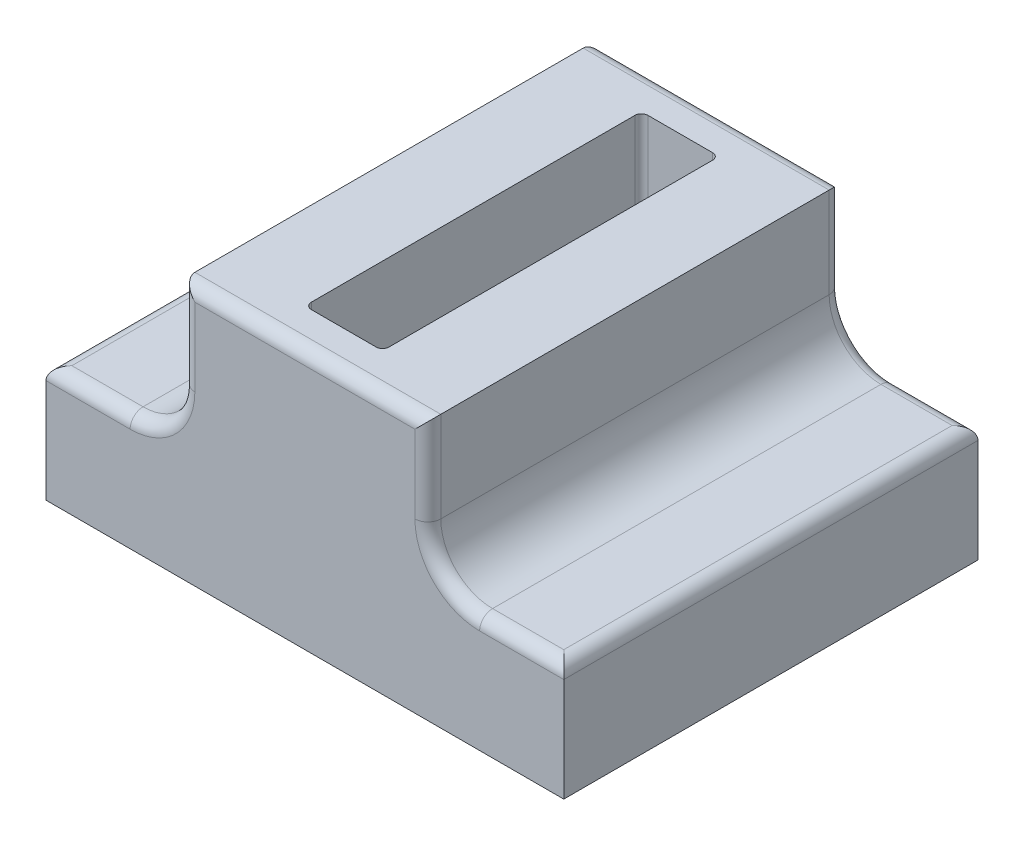
SolidWorks part; units mm, degrees
ref_plane "Front Plane" through (0, 0, 0) normal (0, 0, 1) x (1, 0, 0)
ref_plane "Top Plane" through (0, 0, 0) normal (0, 1, 0) x (1, 0, 0)
ref_plane "Right Plane" through (0, 0, 0) normal (1, 0, 0) x (0, 0, -1)
sketch "Sketch1" plane through (0, 0, 0) normal (0, 1, 0) x (1, 0, 0)
  line L1 (0, 0) -> (20, 0)
  line L2 (0, 0) -> (0, -16)
  line L3 (0, -16) -> (20, -16)
  line L4 (20, 0) -> (20, -16)
  line L6 (8.5, -14.5) -> (11.5, -14.5)
  line L7 (8.5, -1.5) -> (11.5, -1.5)
  line L8 (8.5, -1.5) -> (8.5, -14.5)
  line L9 (11.5, -1.5) -> (11.5, -14.5)
extrude "Boss-Extrude1" add sketch "Sketch1" along normal blind 4.5
sketch "Sketch2" plane through (0, 4.5, 0) normal (0, 1, 0) x (1, 0, 0)
  line L0 (5.25, 0) -> (14.75, 0)
  line L3 (5.25, 0) -> (5.25, -16)
  line L4 (14.75, 0) -> (14.75, -16)
  line L5 (5.25, -16) -> (14.75, -16)
  line L7 (8.5, -1.5) -> (11.5, -1.5)
  line L8 (8.5, -1.5) -> (8.5, -14.5)
  line L9 (8.5, -14.5) -> (11.5, -14.5)
  line L10 (11.5, -1.5) -> (11.5, -14.5)
extrude "Boss-Extrude2" add sketch "Sketch2" along normal blind 5.5
fillet "Fillet1" radius 2 2 edges at (5.25, 4.5, 8) (14.75, 4.5, 8)
fillet "Fillet2" radius 0.5 16 edges at (1.625, 4.5, 0) (5.25, 8.25, 0) (14.75, 8.25, 0) (18.375, 4.5, 0) (18.375, 4.5, 16) (14.75, 8.25, 16) (5.25, 8.25, 16) (4.6642, 5.0858, 16) (0, 4.5, 8) (20, 4.5, 8) (10, 10, 0) (4.6642, 5.0858, 0) (15.3358, 5.0858, 0) (15.3358, 5.0858, 16) (10, 10, 16) (1.625, 4.5, 16)
fillet "Fillet3" radius 0.25 4 edges at (8.5, 5, 14.5) (11.5, 5, 14.5) (11.5, 5, 1.5) (8.5, 5, 1.5)
